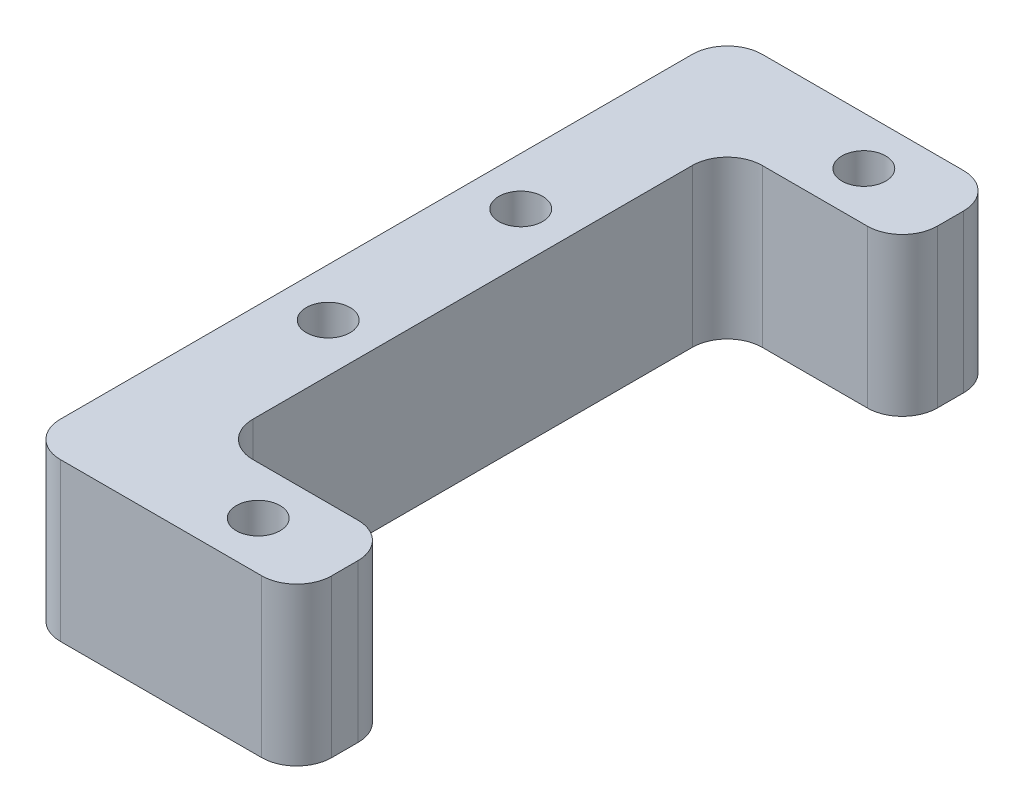
SolidWorks part; units mm, degrees
ref_plane "Front" through (0, 0, 0) normal (0, 0, 1) x (1, 0, 0)
ref_plane "Top" through (0, 0, 0) normal (0, 1, 0) x (1, 0, 0)
ref_plane "Right" through (0, 0, 0) normal (1, 0, 0) x (0, 0, -1)
sketch "Sketch1" plane through (0, 0, 0) normal (0, 1, 0) x (1, 0, 0)
  line L0 (0, 0) -> (5.5, 0) construction
  line L1 (0, -20.05) -> (0, 20.05)
  line L2 (0, 20.05) -> (15.5, 20.05)
  line L3 (15.5, 20.05) -> (15.5, 14.55)
  line L4 (15.5, 14.55) -> (5.5, 14.55)
  line L5 (5.5, 14.55) -> (5.5, -14.55)
  line L6 (2.75, 5.5) -> (2.75, -5.5) construction
  line L7 (2.75, 5.5) -> (2.75, 20.05) construction
  line L8 (10.55, 17.3) -> (15.5, 17.3) construction
  line L9 (10.55, 17.3) -> (0, 17.3) construction
  line L10 (10.55, -17.3) -> (0, -17.3) construction
  line L11 (10.55, -17.3) -> (15.5, -17.3) construction
  line L12 (2.75, -5.5) -> (2.75, -20.05) construction
  line L13 (15.5, -14.55) -> (5.5, -14.55)
  line L14 (15.5, -20.05) -> (15.5, -14.55)
  line L15 (0, -20.05) -> (15.5, -20.05)
  circle A0 centre (2.75, 5.5) radius 1.25
  circle A1 centre (10.55, 17.3) radius 1.25
  circle A2 centre (10.55, -17.3) radius 1.25
  circle A3 centre (2.75, -5.5) radius 1.25
  point P16 (3.0811, 0)
  point P21 (2.75, 0)
  dimension "D1" = 2.5
  dimension "D2" = 5.5
  dimension "D3" = 5.5
  dimension "D4" = 17.3
  dimension "D5" = 7.8
  dimension "D6" = 5.5
  dimension "D7" = 10
extrude "Boss-Extrude1" add sketch "Sketch1" along normal blind 9
fillet "Fillet1" radius 2 8 edges at (15.5, 4.5, -20.05) (15.5, 4.5, -14.55) (15.5, 4.5, 14.55) (15.5, 4.5, 20.05) (0, 4.5, 20.05) (0, 4.5, -20.05) (5.5, 4.5, -14.55) (5.5, 4.5, 14.55)
